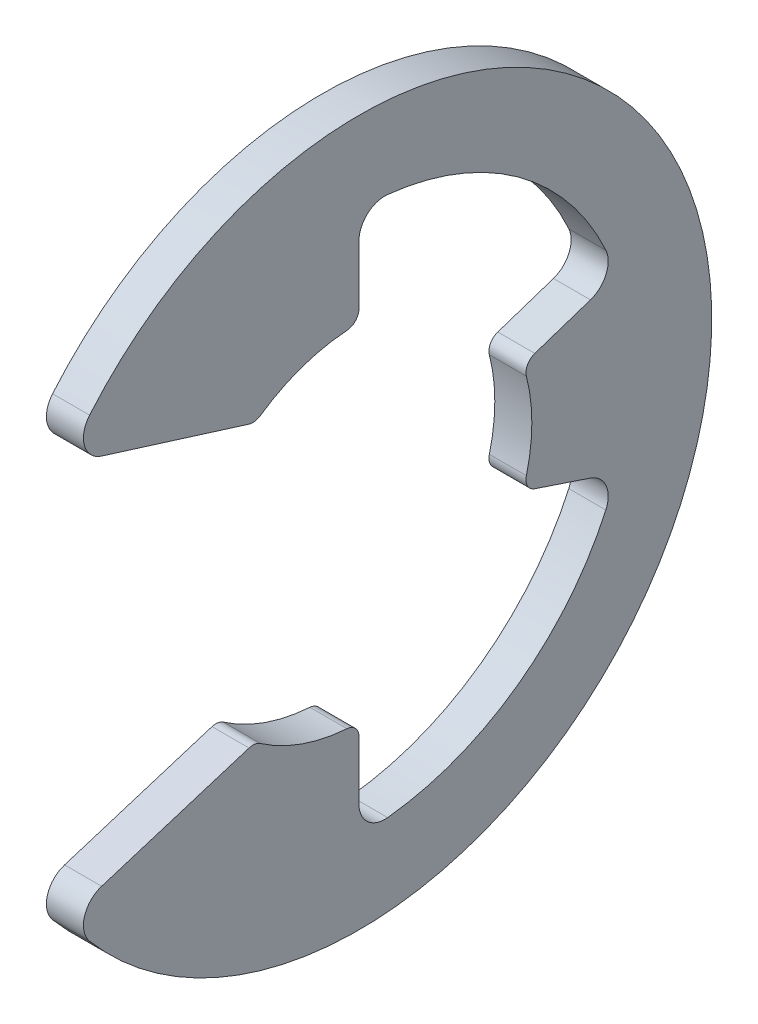
SolidWorks part; units mm, degrees
material "Plain Carbon Steel"
ref_plane "Front" through (0, 0, 0) normal (0, 0, 1) x (1, 0, 0)
ref_plane "Top" through (0, 0, 0) normal (0, 1, 0) x (1, 0, 0)
ref_plane "Right" through (0, 0, 0) normal (1, 0, 0) x (0, 0, -1)
sketch "Sketch1" plane through (0, 0, 0) normal (1, 0, 0) x (0, 0, -1)
  line L0 (-8.4234, -5.6809) -> (-2.987, -3.9827)
  line L1 (-8.4234, 5.6809) -> (-2.987, 3.9827)
  line L2 (0, -4.9784) -> (0, -7.8134)
  line L3 (0, 4.9784) -> (0, 7.8134)
  line L4 (4.7229, -1.5743) -> (7.4124, -2.4708)
  line L5 (4.7229, 1.5743) -> (7.4124, 2.4708)
  line L6 (0, 0) -> (-4.9784, 0) construction
  line L7 (4.7229, 1.5743) -> (4.7229, -1.5743) construction
  line L8 (0, -4.9784) -> (-2.987, -3.9827) construction
  line L9 (0, 10.16) -> (0, -10.16) construction
  circle A2 centre (0, 0) radius 4.9784 construction
  arc A3 (-8.4234, -5.6809) -> (-8.4234, 5.6809) centre (0, 0) ccw
  arc A4 (-2.987, -3.9827) -> (0, -4.9784) centre (0, 0) ccw
  arc A5 (-2.987, 3.9827) -> (0, 4.9784) centre (0, 0) cw
  arc A6 (4.7229, 1.5743) -> (4.7229, -1.5743) centre (0, 0) cw
  arc A7 (0, -7.8134) -> (7.4124, -2.4708) centre (0, 0) ccw
  arc A8 (7.4124, 2.4708) -> (0, 7.8134) centre (0, 0) ccw
  point P8 (0, 4.9784)
  point P12 (0, 10.16)
  dimension "Free Diameter" = 9.9568
  dimension "D1" = 7.8134
  dimension "Ring OD" = 20.32
  dimension "D2" = 5.8218
  dimension "D10" = 7.9654
sketch "Sketch4" plane through (0, 0, 0) normal (0, 0, 1) x (1, 0, 0)
  line L0 (-0.5334, 10.16) -> (0.5334, 10.16) construction
  point P3 (0, 10.16)
  dimension "Ring Thickness" = 1.0668
sketch "Sketch3" plane through (0, 0, 0) normal (1, 0, 0) x (0, 0, -1)
  line L6 (4.7229, -1.5743) -> (7.4124, -2.4708)
  line L7 (0, -7.8134) -> (0, -4.9784)
  line L8 (-2.987, -3.9827) -> (-8.4234, -5.6809)
  line L9 (-8.4234, 5.6809) -> (-2.987, 3.9827)
  line L10 (0, 4.9784) -> (0, 7.8134)
  line L11 (7.4124, 2.4708) -> (4.7229, 1.5743)
  line L12 (4.7229, -1.5743) -> (7.4124, -2.4708)
  line L13 (0, -7.8134) -> (0, -4.9784)
  line L14 (-2.987, -3.9827) -> (-8.4234, -5.6809)
  line L15 (-8.4234, 5.6809) -> (-2.987, 3.9827)
  line L16 (0, 4.9784) -> (0, 7.8134)
  line L17 (7.4124, 2.4708) -> (4.7229, 1.5743)
  arc A6 (0, -7.8134) -> (7.4124, -2.4708) centre (0, 0) ccw
  arc A7 (-2.987, -3.9827) -> (0, -4.9784) centre (0, 0) ccw
  arc A8 (-8.4234, -5.6809) -> (-8.4234, 5.6809) centre (0, 0) ccw
  arc A9 (0, 4.9784) -> (-2.987, 3.9827) centre (0, 0) ccw
  arc A10 (7.4124, 2.4708) -> (0, 7.8134) centre (0, 0) ccw
  arc A11 (4.7229, -1.5743) -> (4.7229, 1.5743) centre (0, 0) ccw
  arc A12 (0, -7.8134) -> (7.4124, -2.4708) centre (0, 0) ccw
  arc A13 (-2.987, -3.9827) -> (0, -4.9784) centre (0, 0) ccw
  arc A14 (-8.4234, -5.6809) -> (-8.4234, 5.6809) centre (0, 0) ccw
  arc A15 (0, 4.9784) -> (-2.987, 3.9827) centre (0, 0) ccw
  arc A16 (7.4124, 2.4708) -> (0, 7.8134) centre (0, 0) ccw
  arc A17 (4.7229, -1.5743) -> (4.7229, 1.5743) centre (0, 0) ccw
  dimension "D1" = 0
extrude "Boss-Extrude1" add sketch "Sketch3" along normal up to vertex (0.5334 mm away) and the other way up to vertex (0.5334 mm away) up to point (0.5334, 10.16, 0) other way up to point (-0.5334, 10.16, 0)
fillet "Fillet1" radius 0.7468 6 edges at (0, -7.8134, 0) (0, -2.4708, -7.4124) (0, 2.4708, -7.4124) (0, 7.8134, 0) (0, -5.6809, 8.4234) (0, 5.6809, 8.4234)
fillet "Fillet2" radius 0.3734 6 edges at (0, -4.9784, 0) (0, -3.9827, 2.987) (0, 1.5743, -4.7229) (0, -1.5743, -4.7229) (0, 3.9827, 2.987) (0, 4.9784, 0)
equation "\"D1@Sketch1\" =  ( \"Ring OD@Sketch1\" + \"Free Diameter@Sketch1\" )  / 3.875"
equation "\"D10@Sketch1\"=\"Free Diameter@Sketch1\" * .8"
equation "\"D1@Fillet1\"=\"Ring Thickness@Sketch4\"*.7"
equation "\"D1@Fillet2\"=\"D1@Fillet1\"/2"
